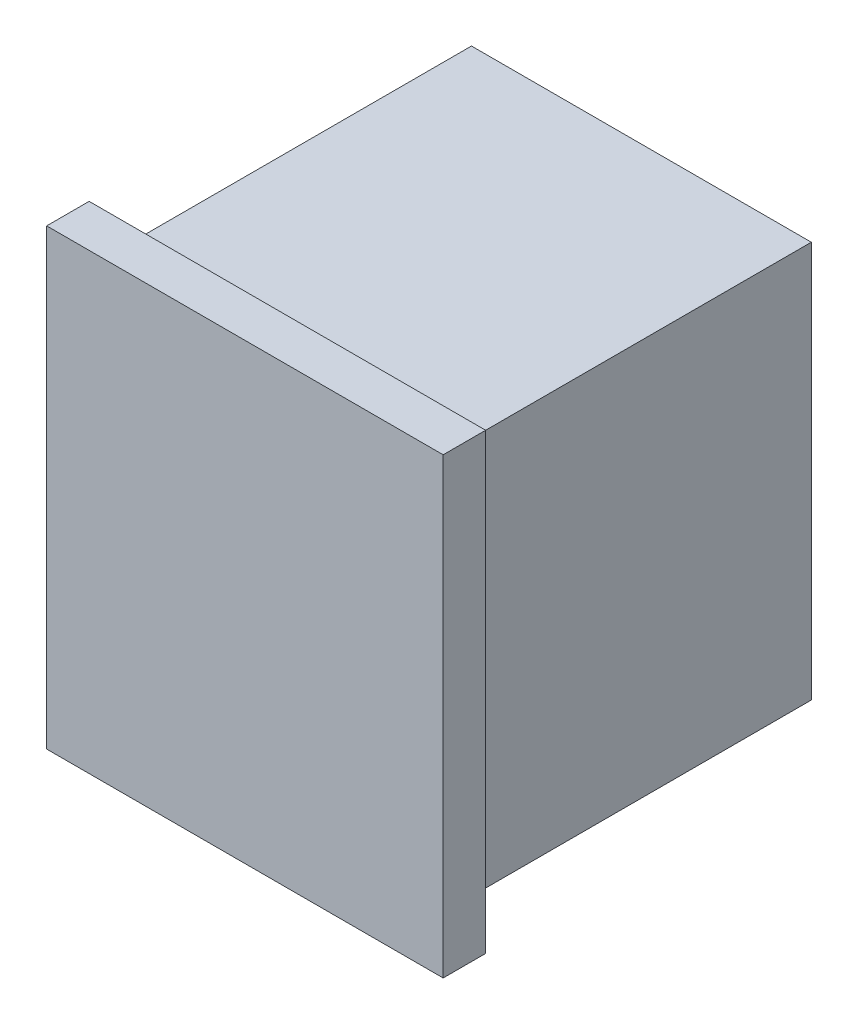
SolidWorks part; units mm, degrees
ref_plane "Спереди" through (0, 0, 0) normal (0, 0, 1) x (1, 0, 0)
ref_plane "Сверху" through (0, 0, 0) normal (0, 1, 0) x (1, 0, 0)
ref_plane "Справа" through (0, 0, 0) normal (1, 0, 0) x (0, 0, -1)
sketch "Эскиз1" plane through (0, 0, 0) normal (0, 0, 1) x (1, 0, 0)
  line L1 (14, -16) -> (-14, -16)
  line L2 (14, -16) -> (14, 16)
  line L3 (14, 16) -> (-14, 16)
  line L4 (-14, -16) -> (-14, 16)
  line L5 (14, -16) -> (-14, 16) construction
  line L6 (14, 16) -> (-14, -16) construction
  point P0 (0, 0)
  dimension "D1" = 28
  dimension "D2" = 32
extrude "Бобышка-Вытянуть1" add sketch "Эскиз1" along normal blind 3
sketch "Эскиз2" plane through (0, 0, 0) normal (0, 0, -1) x (-1, 0, 0)
  line L4 (14, -16) -> (14, 16)
  line L5 (14, 16) -> (-14, 16)
  line L6 (-14, 16) -> (-14, -16)
  line L7 (-14, -16) -> (14, -16)
  line L8 (14, -16) -> (14, 16) construction
  line L9 (14, 16) -> (-14, 16) construction
  line L10 (-14, 16) -> (-14, -16) construction
  line L11 (-14, -16) -> (14, -16) construction
  line L16 (12, -14) -> (12, 14)
  line L17 (12, 14) -> (-12, 14)
  line L18 (-12, 14) -> (-12, -14)
  line L19 (-12, -14) -> (12, -14)
  line L20 (12, -14) -> (12, 14)
  line L21 (12, 14) -> (-12, 14)
  line L22 (-12, 14) -> (-12, -14)
  line L23 (-12, -14) -> (12, -14)
  dimension "D1" = 0
  dimension "D2" = 2
extrude "Бобышка-Вытянуть2" add sketch "Эскиз2" along normal blind 25
